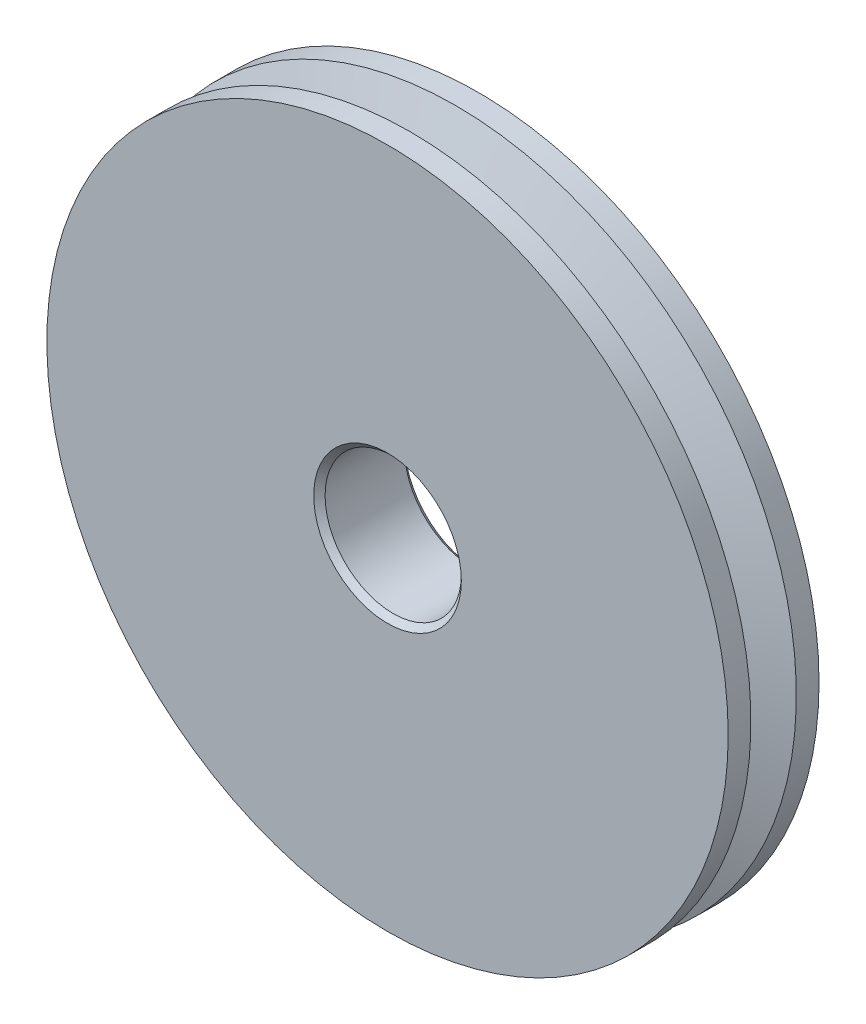
SolidWorks part; units mm, degrees
material "6061-T6 (SS)"
ref_plane "Front Plane" through (0, 0, 0) normal (0, 0, 1) x (1, 0, 0)
ref_plane "Top Plane" through (0, 0, 0) normal (0, 1, 0) x (1, 0, 0)
ref_plane "Right Plane" through (0, 0, 0) normal (1, 0, 0) x (0, 0, -1)
sketch "Sketch1" plane through (0, 0, 0) normal (0, 0, 1) x (1, 0, 0)
  circle A0 centre (0, 0) radius 47.625
  circle A1 centre (0, 0) radius 9.525
  dimension "D1" = 95.25
  dimension "D2" = 19.05
extrude "Extrude1" add sketch "Sketch1" along normal mid plane 12.7
sketch "Sketch2" plane through (0, 0, 0) normal (1, 0, 0) x (0, 0, -1)
  line L0 (-3.175, 47.625) -> (3.175, 47.625)
  line L2 (3.175, 47.625) -> (0.8638, 41.275)
  line L3 (0.8638, 41.275) -> (-0.8638, 41.275)
  line L4 (-0.8638, 41.275) -> (-3.175, 47.625)
  line L5 (-6.35, 0) -> (6.35, 0) construction
  line L6 (-6.35, 47.625) -> (-6.35, -47.625) construction
  line L7 (6.35, -47.625) -> (6.35, 47.625) construction
  point P2 (0, 47.625)
  point P5 (0, 41.275)
  dimension "D1" = 47.625
  dimension "D2" = 6.35
  dimension "D3" = 6.35
  dimension "D4" = 40
chamfer "Chamfer1" distance 0.7937 angle 45 2 edges at (9.525, 0, -6.35) (9.525, 0, 6.35)
revolve "Cut-Revolve1" cut sketch "Sketch2" angle 360 about L5
